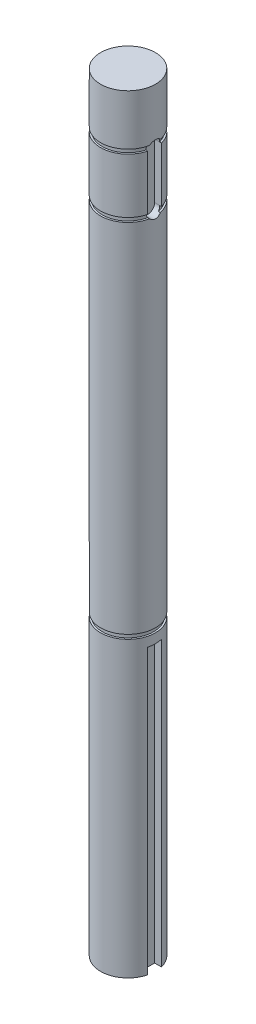
SolidWorks part; units mm, degrees
ref_plane "Front Plane" through (0, 0, 0) normal (0, 0, 1) x (1, 0, 0)
ref_plane "Top Plane" through (0, 0, 0) normal (0, 1, 0) x (1, 0, 0)
ref_plane "Right Plane" through (0, 0, 0) normal (1, 0, 0) x (0, 0, -1)
sketch "Sketch1" plane through (0, 0, 0) normal (0, 1, 0) x (1, 0, 0)
  circle A0 centre (0, 0) radius 2.5
extrude "Boss-Extrude1" add sketch "Sketch1" along normal blind 70 contours A0
sketch "Sketch2" plane through (0, 0, 0) normal (1, 0, 0) x (0, 0, -1)
  line L0 (2.5, 70) -> (-2.5, 70) construction
  line L1 (-10.3427, 65.39) -> (-2.34, 65.39)
  line L2 (-10.3427, 65.39) -> (-10.3427, 65)
  line L3 (-10.3427, 65) -> (-2.34, 65)
  line L4 (-2.34, 65.39) -> (-2.34, 65)
  line L5 (-2.5, 70) -> (-2.5, 0) construction
  line L6 (0, 67.1457) -> (0, 63.1805) construction
  dimension "D1" = 4.61
  dimension "D2" = 0.39
  dimension "D3" = 0.16
revolve "Cut-Revolve1" cut sketch "Sketch2" angle 360 about L6
sketch "Sketch3" plane through (0, 0, 0) normal (1, 0, 0) x (0, 0, -1)
  line L0 (2.5, 65) -> (-2.5, 65) construction
  line L1 (-14.1547, 60) -> (-2.34, 60)
  line L2 (-14.1547, 60) -> (-14.1547, 59.61)
  line L3 (-14.1547, 59.61) -> (-2.34, 59.61)
  line L4 (-2.34, 60) -> (-2.34, 59.61)
  line L5 (-2.5, 65) -> (-2.5, 0) construction
  line L6 (0, 61.0146) -> (0, 57.5191) construction
  dimension "D1" = 5
  dimension "D2" = 0.39
  dimension "D3" = 0.16
revolve "Cut-Revolve2" cut sketch "Sketch3" angle 360 about L6
sketch "Sketch4" plane through (0, 0, 0) normal (1, 0, 0) x (0, 0, -1)
  line L0 (2.5, 59.61) -> (-2.5, 59.61) construction
  line L1 (-14.9775, 27.11) -> (-2.34, 27.11)
  line L2 (-14.9775, 27.11) -> (-14.9775, 26.72)
  line L3 (-14.9775, 26.72) -> (-2.34, 26.72)
  line L4 (-2.34, 27.11) -> (-2.34, 26.72)
  line L5 (-2.5, 59.61) -> (-2.5, 0) construction
  line L6 (0, 27.3415) -> (0, 24.803) construction
  dimension "D1" = 32.5
  dimension "D2" = 0.39
  dimension "D3" = 0.16
revolve "Cut-Revolve3" cut sketch "Sketch4" angle 360 about L6
ref_plane "Plane1" through (2.5, 0, 0) normal (1, 0, 0) x (0, 0, -1)
sketch "Sketch5" plane through (2.5, 0, 0) normal (1, 0, 0) x (0, 0, -1)
  line L0 (0, 65) -> (0, 60) construction
  line L1 (2.5, 65) -> (-2.5, 65) construction
  line L2 (-2.34, 60) -> (2.34, 60) construction
  line L3 (0.625, 65) -> (0.625, 60)
  line L4 (-0.625, 65) -> (-0.625, 60)
  arc A0 (0.625, 65) -> (-0.625, 65) centre (0, 65) ccw
  arc A1 (-0.625, 60) -> (0.625, 60) centre (0, 60) ccw
  point P6 (0, 62.5)
extrude "Cut-Extrude1" cut sketch "Sketch5" against normal blind 0.7 contours L4 A1 L3 A0
sketch "Sketch6" plane through (2.5, 0, 0) normal (1, 0, 0) x (0, 0, -1)
  line L0 (-2.5, 26.72) -> (-2.5, 0) construction
  line L1 (-0.625, 25.86) -> (0.625, 25.86)
  line L2 (-0.625, 25.86) -> (-0.625, -5.7669)
  line L3 (-0.625, -5.7669) -> (0.625, -5.7669)
  line L4 (0.625, 25.86) -> (0.625, -5.7669)
  line L5 (2.5, 26.72) -> (-2.5, 26.72) construction
  dimension "D1" = 1.875
  dimension "D2" = 1.25
  dimension "D3" = 0.86
extrude "Cut-Extrude2" cut sketch "Sketch6" against normal blind 0.7 contours L4 L3 L2 L1
